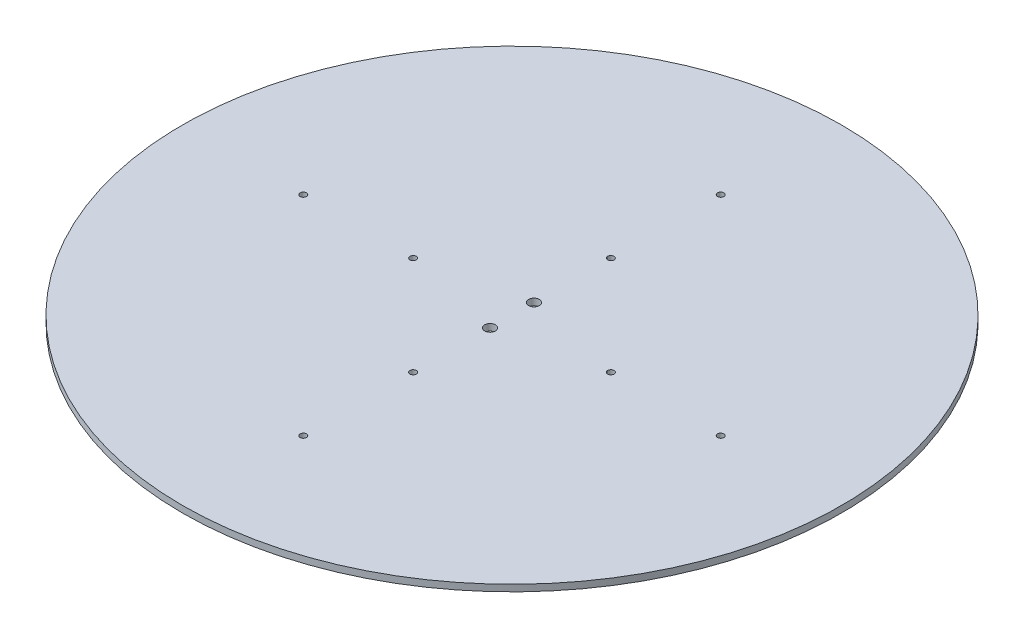
SolidWorks part; units mm, degrees
material "ABS"
ref_plane "Front Plane" through (0, 0, 0) normal (0, 0, 1) x (1, 0, 0)
ref_plane "Top Plane" through (0, 0, 0) normal (0, 1, 0) x (1, 0, 0)
ref_plane "Right Plane" through (0, 0, 0) normal (1, 0, 0) x (0, 0, -1)
sketch "Sketch1" plane through (0, 0, 0) normal (0, 1, 0) x (1, 0, 0)
  line L0 (0, 0) -> (16.3373, 0)
  line L1 (0, 0) -> (0, -5.6826)
  circle A0 centre (0, 0) radius 150
  circle A2 centre (0, 10) radius 2.45
  circle A3 centre (0, -10) radius 2.45
  circle A4 centre (45, 0) radius 1.45
  circle A5 centre (95, 0) radius 1.45
  circle A6 centre (0, -45) radius 1.45
  circle A7 centre (0, -95) radius 1.45
  circle A8 centre (-95, 0) radius 1.45
  circle A9 centre (-45, 0) radius 1.45
  circle A10 centre (0, 95) radius 1.45
  circle A11 centre (0, 45) radius 1.45
  dimension "D1" = 300
  dimension "D2" = 4.9
  dimension "D5" = 2.9
  dimension "D10" = 2.9
  dimension "D3" = 20
  dimension "D4" = 10
  dimension "D6" = 45
  dimension "D7" = 50
  dimension "D8" = 45
  dimension "D9" = 50
extrude "Boss-Extrude1" add sketch "Sketch1" along normal blind 3
